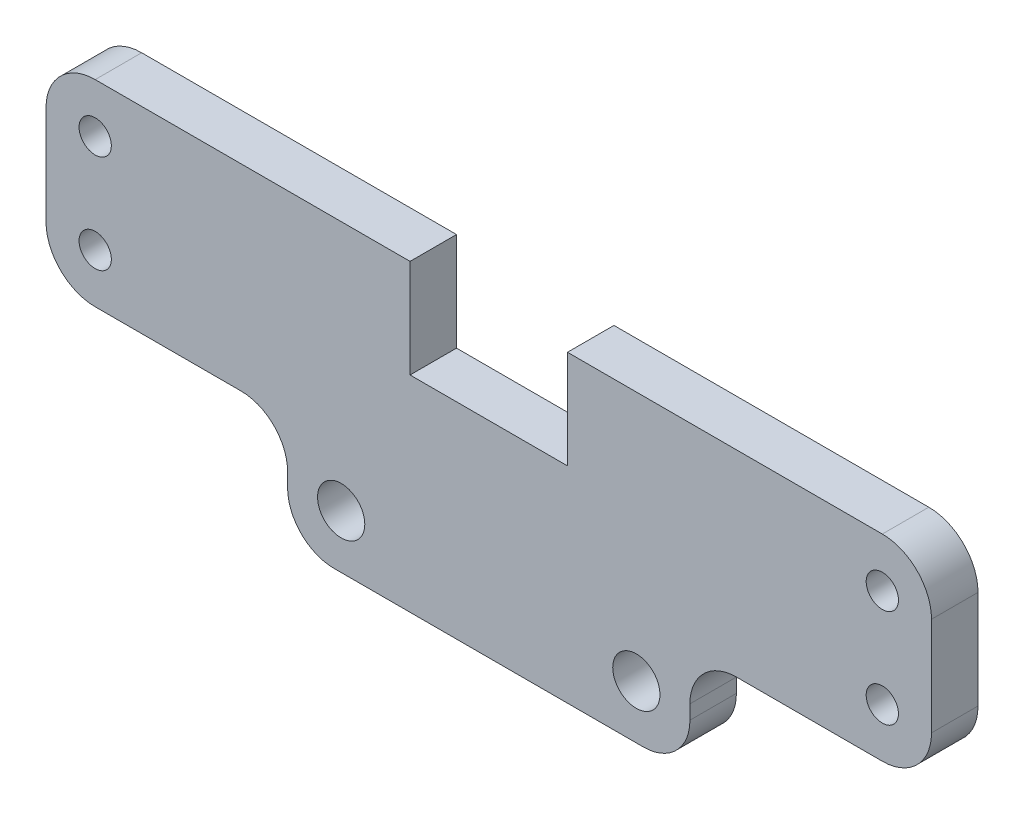
SolidWorks part; units mm, degrees
ref_plane "Front Plane" through (0, 0, 0) normal (0, 0, 1) x (1, 0, 0)
ref_plane "Top Plane" through (0, 0, 0) normal (0, 1, 0) x (1, 0, 0)
ref_plane "Right Plane" through (0, 0, 0) normal (1, 0, 0) x (0, 0, -1)
sketch "Sketch1" plane through (0, 0, 0) normal (0, 0, 1) x (1, 0, 0)
  line L0 (-82.0738, -16.6688) -> (19.5263, -16.6688)
  line L1 (-82.0738, -42.0688) -> (19.5263, -42.0688)
  line L2 (-31.2738, -16.6688) -> (-31.2738, -42.0688) construction
  line L56 (-88.4238, -23.0188) -> (-88.4237, -35.7188)
  line L57 (-82.0738, -42.0688) -> (-66.1987, -42.0688)
  line L94 (-26.8287, 18.3197) -> (-26.8287, 31.0197)
  line L96 (-26.8287, 31.0197) -> (-35.7187, 31.0197)
  line L98 (-35.7187, 31.0197) -> (-35.7188, 18.3197)
  line L100 (-35.7188, 18.3197) -> (-97.3138, 18.3197)
  line L106 (25.8763, -35.7188) -> (25.8763, -23.0188)
  line L107 (32.2263, -16.6688) -> (34.7663, -16.6688)
  line L108 (41.1163, -10.3188) -> (41.1163, 11.9697)
  line L109 (34.7663, 18.3197) -> (-26.8287, 18.3197)
  line L110 (-103.6638, 11.9697) -> (-103.6638, -10.3188)
  line L111 (-97.3138, -16.6688) -> (-94.7738, -16.6688)
  line L112 (-88.4238, -23.0188) -> (-88.4237, -35.7188)
  line L158 (-28.0987, -42.0688) -> (-28.0987, -36.4681)
  line L160 (-28.0987, -36.4681) -> (-29.6862, -36.4681)
  line L162 (25.8763, -35.7188) -> (25.8763, -23.0188)
  line L224 (-29.6862, -36.4681) -> (-29.6862, -34.1313)
  line L226 (-29.6862, -34.1313) -> (-28.0987, -34.1313)
  line L228 (-28.0987, -34.1313) -> (-28.0987, -32.8613)
  line L230 (-28.0987, -32.8613) -> (-24.9237, -32.8613)
  line L232 (-24.9237, -32.8613) -> (-24.9237, -34.1313)
  line L234 (-24.9237, -34.1313) -> (-23.3362, -34.1313)
  line L236 (-23.3362, -34.1313) -> (-23.3362, -36.4681)
  line L238 (-23.3362, -36.4681) -> (-24.9237, -36.4681)
  line L240 (-24.9237, -36.4681) -> (-24.9237, -42.0688)
  line L242 (-24.9237, -42.0688) -> (0.4762, -42.0688)
  line L244 (0.4762, -42.0688) -> (0.4762, -36.4681)
  line L246 (0.4762, -36.4681) -> (-1.1113, -36.4681)
  line L248 (-1.1113, -36.4681) -> (-1.1113, -34.1313)
  line L250 (-1.1113, -34.1313) -> (0.4762, -34.1313)
  line L252 (0.4762, -34.1313) -> (0.4762, -32.8613)
  line L254 (0.4762, -32.8613) -> (3.6512, -32.8613)
  line L256 (3.6512, -32.8613) -> (3.6512, -34.1313)
  line L258 (3.6512, -34.1313) -> (5.2387, -34.1313)
  line L260 (5.2387, -34.1313) -> (5.2387, -36.4681)
  line L262 (5.2387, -36.4681) -> (3.6512, -36.4681)
  line L264 (3.6512, -36.4681) -> (3.6512, -42.0688)
  line L266 (3.6512, -42.0688) -> (19.5263, -42.0688)
  line L268 (-66.1987, -42.0688) -> (-66.1987, -36.4681)
  line L270 (-66.1987, -36.4681) -> (-67.7862, -36.4681)
  line L272 (-67.7862, -36.4681) -> (-67.7862, -34.1313)
  line L274 (-67.7862, -34.1313) -> (-66.1987, -34.1313)
  line L276 (-66.1987, -34.1313) -> (-66.1987, -32.8613)
  line L278 (-66.1987, -32.8613) -> (-63.0237, -32.8613)
  line L280 (-63.0237, -32.8613) -> (-63.0237, -34.1313)
  line L282 (-63.0237, -34.1313) -> (-61.4362, -34.1313)
  line L284 (-61.4362, -34.1313) -> (-61.4362, -36.4681)
  line L286 (-61.4362, -36.4681) -> (-63.0237, -36.4681)
  line L288 (-63.0237, -36.4681) -> (-63.0237, -42.0688)
  line L290 (-63.0237, -42.0688) -> (-37.6237, -42.0688)
  line L292 (-37.6237, -42.0688) -> (-37.6237, -36.4681)
  line L294 (-37.6237, -36.4681) -> (-39.2112, -36.4681)
  line L296 (-39.2112, -36.4681) -> (-39.2112, -34.1313)
  line L298 (-39.2112, -34.1313) -> (-37.6237, -34.1313)
  line L300 (-37.6237, -34.1313) -> (-37.6237, -32.8612)
  line L302 (-37.6237, -32.8612) -> (-34.4487, -32.8612)
  line L304 (-34.4487, -32.8612) -> (-34.4487, -34.1313)
  line L306 (-34.4487, -34.1313) -> (-32.8612, -34.1313)
  line L308 (-32.8612, -34.1313) -> (-32.8612, -36.4681)
  line L310 (-32.8612, -36.4681) -> (-34.4487, -36.4681)
  line L312 (-34.4487, -36.4681) -> (-34.4487, -42.0687)
  line L314 (-34.4487, -42.0687) -> (-28.0987, -42.0688)
  circle A0 centre (-82.0738, -23.0188) radius 2.0828 construction
  circle A1 centre (19.5263, -23.0188) radius 2.0828 construction
  circle A2 centre (-82.0738, -23.0188) radius 2.0828
  circle A3 centre (19.5263, -23.0188) radius 2.0828
  arc A4 (-88.4238, -23.0188) -> (-82.0738, -16.6688) centre (-82.0738, -23.0187) cw
  arc A5 (19.5263, -16.6688) -> (25.8763, -23.0188) centre (19.5263, -23.0188) cw
  circle A6 centre (-82.0738, -35.7188) radius 2.0828 construction
  circle A7 centre (19.5263, -35.7188) radius 2.0828 construction
  arc A8 (-88.4237, -35.7188) -> (-82.0738, -42.0688) centre (-82.0738, -35.7188) ccw
  arc A9 (19.5263, -42.0688) -> (25.8763, -35.7188) centre (19.5263, -35.7188) ccw
  arc A10 (32.2263, -16.6688) -> (25.8763, -23.0188) centre (32.2263, -23.0188) ccw
  arc A11 (34.7663, -16.6688) -> (41.1163, -10.3188) centre (34.7663, -10.3188) ccw
  arc A12 (41.1163, 11.9697) -> (34.7663, 18.3197) centre (34.7663, 11.9697) ccw
  arc A13 (-97.3138, 18.3197) -> (-103.6638, 11.9697) centre (-97.3138, 11.9697) ccw
  arc A14 (-103.6638, -10.3188) -> (-97.3138, -16.6688) centre (-97.3138, -10.3188) ccw
  arc A15 (-88.4238, -23.0188) -> (-94.7738, -16.6688) centre (-94.7738, -23.0188) ccw
  arc A16 (-88.4237, -35.7188) -> (-82.0738, -42.0688) centre (-82.0738, -35.7188) ccw
  arc A17 (19.5263, -42.0688) -> (25.8763, -35.7188) centre (19.5263, -35.7188) ccw
  circle A18 centre (-82.0738, -35.7188) radius 2.0828
  circle A19 centre (19.5263, -35.7188) radius 2.0828
  dimension "D1" = 0
extrude "Boss-Extrude1" add sketch "Sketch1" along normal mid plane 6
sketch "Sketch2" plane through (0, 0, 3) normal (0, 0, 1) x (1, 0, 0)
  line L0 (19.5263, -16.6688) -> (-82.0738, -16.6688) construction
  line L1 (-21.1138, -16.6687) -> (-41.4338, -16.6688)
  line L2 (-21.1138, -16.6687) -> (-21.1138, -29.3687)
  line L3 (-21.1138, -29.3687) -> (-41.4338, -29.3688)
  line L4 (-41.4338, -16.6688) -> (-41.4338, -29.3688)
  point P6 (-31.2738, -16.6687)
  dimension "D1" = 12.7
  dimension "D2" = 20.32
extrude "Cut-Extrude1" cut sketch "Sketch2" against normal through all
sketch "Sketch3" plane through (0, 0, 3) normal (0, 0, 1) x (1, 0, 0)
  line L0 (-31.2738, -29.3687) -> (-31.2738, -42.0688) construction
  line L1 (-41.4338, -29.3688) -> (-21.1138, -29.3687) construction
  line L2 (-82.0738, -42.0688) -> (19.5263, -42.0688) construction
  line L3 (-57.2385, -55.8983) -> (-31.2738, -55.8983)
  line L4 (-57.2385, -55.8983) -> (-43.409, -55.8983) construction
  line L5 (-57.2385, -55.8983) -> (-57.2385, -42.0688)
  line L6 (-57.2385, -42.0688) -> (-43.409, -42.0688) construction
  line L7 (-43.409, -55.8983) -> (-43.409, -42.0688) construction
  line L8 (-57.2385, -55.8983) -> (-43.409, -42.0688) construction
  line L9 (-57.2385, -42.0688) -> (-43.409, -55.8983) construction
  line L10 (-31.2738, -55.8983) -> (-31.2738, -42.0688)
  line L11 (-31.2738, -42.0688) -> (-57.2385, -42.0688)
  circle A0 centre (-50.3238, -48.9835) radius 3.048
  point P6 (-50.3238, -48.9835)
  dimension "D3" = 6.096
  dimension "D1" = 19.558
  dimension "D2" = 19.05
extrude "Boss-Extrude2" add sketch "Sketch3" against normal blind 6
fillet "Fillet1" radius 6 2 edges at (-57.2385, -55.8983, 0) (-57.2385, -42.0688, 0)
mirror "Mirror1" about plane through (-31.2738, -55.8983, -3) normal (1, 0, 0) of "Fillet1", "Boss-Extrude2"
